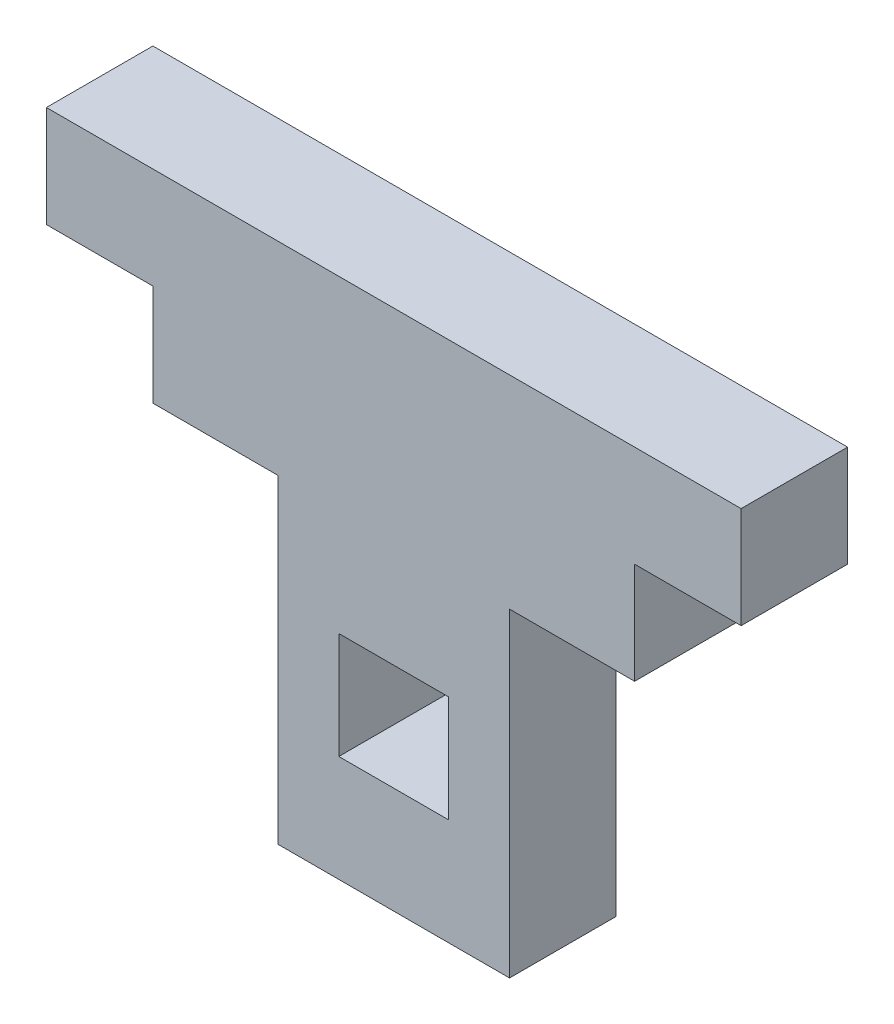
SolidWorks part; units mm, degrees
ref_plane "Front Plane" through (0, 0, 0) normal (0, 0, 1) x (1, 0, 0)
ref_plane "Top Plane" through (0, 0, 0) normal (0, 1, 0) x (1, 0, 0)
ref_plane "Right Plane" through (0, 0, 0) normal (1, 0, 0) x (0, 0, -1)
sketch "Sketch1" plane through (0, 0, 0) normal (0, 0, 1) x (1, 0, 0)
  line L5 (0, 0) -> (24.13, 0)
  line L6 (0, 0) -> (0, 10.16)
  line L7 (0, 10.16) -> (24.13, 10.16)
  line L8 (24.13, 0) -> (24.13, 10.16)
  dimension "D1" = 24.13
  dimension "D2" = 10.16
extrude "Boss-Extrude1" add sketch "Sketch1" along normal blind 5.334 contours L6 L5 L8 L7
sketch "Sketch6" plane through (24.13, 0, 0) normal (1, 0, 0) x (0, 0, -1)
  line L9 (-5.334, 0) -> (-5.334, 10.16) construction
  line L10 (-5.334, 10.16) -> (0, 10.16)
  line L11 (-5.334, 10.16) -> (-5.334, 0)
  line L12 (-5.334, 0) -> (0, 0)
  line L13 (0, 10.16) -> (0, 0)
  line L14 (-5.334, 10.16) -> (0, 10.16) construction
extrude "Boss-Extrude5" add sketch "Sketch6" along normal blind 5.334
sketch "Sketch11" plane through (0, 0, 0) normal (-1, 0, 0) x (0, 0, 1)
  line L1 (0, 10.2062) -> (5.334, 10.2062)
  line L2 (0, 10.2062) -> (0, 0)
  line L3 (0, 0) -> (5.334, 0)
  line L4 (5.334, 10.2062) -> (5.334, 0)
extrude "Boss-Extrude6" add sketch "Sketch11" along normal blind 5.334
sketch "Sketch12" plane through (0, 0, 0) normal (0, -1, 0) x (-1, 0, 0)
  line L1 (-29.464, 0) -> (5.334, 0)
  line L2 (-29.464, 0) -> (-29.464, -5.334)
  line L3 (-29.464, -5.334) -> (5.334, -5.334)
  line L4 (5.334, 0) -> (5.334, -5.334)
extrude "Boss-Extrude7" add sketch "Sketch12" along normal blind 5.334
sketch "Sketch13" plane through (0, 0, 0) normal (0, 0, -1) x (-1, 0, 0)
  line L0 (0, 10.16) -> (5.334, 10.16)
  line L1 (5.334, 10.2062) -> (5.334, -5.334) construction
  line L2 (0, 10.16) -> (0, 10.2062)
  line L3 (5.334, 10.2062) -> (0, 10.2062) construction
  line L4 (0, 10.2062) -> (5.334, 10.2062)
  line L5 (5.334, 10.2062) -> (5.334, 10.16)
extrude "Cut-Extrude1" cut sketch "Sketch13" against normal through all
sketch "Sketch17" plane through (0, -5.334, 0) normal (0, -1, 0) x (-1, 0, 0)
  line L0 (-29.464, -5.334) -> (5.334, -5.334) construction
  line L1 (5.334, 0) -> (-6.2653, 0)
  line L2 (5.334, 0) -> (5.334, -5.334)
  line L3 (5.334, -5.334) -> (-6.2653, -5.334)
  line L4 (-6.2653, 0) -> (-6.2653, -5.334)
  line L5 (-17.8647, 0) -> (-6.2653, 0) construction
  line L6 (-29.464, 0) -> (-17.8647, 0)
  line L7 (-29.464, 0) -> (-29.464, -5.334)
  line L8 (-29.464, -5.334) -> (-17.8647, -5.334)
  line L9 (-17.8647, 0) -> (-17.8647, -5.334)
extrude "Cut-Extrude5" cut sketch "Sketch17" against normal blind 5.334
sketch "Sketch18" plane through (0, 0, 5.334) normal (0, 0, 1) x (1, 0, 0)
  line L0 (17.78, 63.5) -> (17.78, 5.08) construction
  line L1 (-5.334, 10.16) -> (0, 10.16)
  line L2 (-5.334, 10.16) -> (-5.334, 5.08)
  line L3 (-5.334, 5.08) -> (0, 5.08)
  line L4 (0, 10.16) -> (0, 5.08)
  line L5 (17.78, 5.08) -> (29.464, 5.08)
  line L6 (17.78, 5.08) -> (17.78, 10.16)
  line L7 (17.78, 10.16) -> (29.464, 10.16)
  line L8 (29.464, 5.08) -> (29.464, 10.16)
extrude "Cut-Extrude6" cut sketch "Sketch18" against normal blind 5.334
sketch "Sketch19" plane through (17.78, 0, 0) normal (1, 0, 0) x (0, 0, -1)
  line L1 (-5.334, 10.16) -> (0, 10.16)
  line L2 (-5.334, 10.16) -> (-5.334, 5.08)
  line L3 (-5.334, 5.08) -> (0, 5.08)
  line L4 (0, 10.16) -> (0, 5.08)
extrude "Boss-Extrude8" add sketch "Sketch19" along normal blind 5.334
sketch "Sketch20" plane through (23.114, 0, 0) normal (1, 0, 0) x (0, 0, -1)
  line L1 (-5.334, 10.16) -> (0, 10.16)
  line L2 (-5.334, 10.16) -> (-5.334, 5.08)
  line L3 (-5.334, 5.08) -> (0, 5.08)
  line L4 (0, 10.16) -> (0, 5.08)
extrude "Boss-Extrude10" add sketch "Sketch20" along normal blind 1.016
sketch "Sketch21" plane through (0, -5.334, 0) normal (0, -1, 0) x (1, 0, 0)
  line L1 (6.2653, 5.334) -> (17.8647, 5.334)
  line L2 (6.2653, 5.334) -> (6.2653, 0)
  line L3 (6.2653, 0) -> (17.8647, 0)
  line L4 (17.8647, 5.334) -> (17.8647, 0)
extrude "Boss-Extrude11" add sketch "Sketch21" along normal blind 10.668
sketch "Sketch22" plane through (0, 0, 5.334) normal (0, 0, 1) x (1, 0, 0)
  line L0 (17.8647, -16.002) -> (6.2653, -16.002) construction
  line L1 (9.3133, -5.334) -> (14.8167, -5.334)
  line L2 (9.3133, -5.334) -> (9.3133, -10.668)
  line L3 (9.3133, -10.668) -> (14.8167, -10.668)
  line L4 (14.8167, -5.334) -> (14.8167, -10.668)
  line L5 (17.8647, 0) -> (17.8647, -16.002) construction
  line L6 (6.2653, 0) -> (6.2653, -16.002) construction
  dimension "D1" = 5.334
  dimension "D2" = 5.334
  dimension "D3" = 3.048
  dimension "D4" = 3.048
extrude "Cut-Extrude7" cut sketch "Sketch22" against normal through all
sketch "Sketch23" plane through (0, 0, 0) normal (-1, 0, 0) x (0, 0, 1)
  line L1 (0, 5.08) -> (5.334, 5.08)
  line L2 (0, 5.08) -> (0, 10.16)
  line L3 (0, 10.16) -> (5.334, 10.16)
  line L4 (5.334, 5.08) -> (5.334, 10.16)
extrude "Boss-Extrude12" add sketch "Sketch23" along normal blind 5.334
sketch "Sketch24" plane through (-5.334, 0, 0) normal (-1, 0, 0) x (0, 0, 1)
  line L0 (5.334, 0) -> (0, 0) construction
  line L1 (5.334, 0) -> (0, 0)
  line L2 (5.334, 0) -> (5.334, 5.08)
  line L3 (5.334, 5.08) -> (0, 5.08)
  line L4 (0, 0) -> (0, 5.08)
  line L5 (0, 10.16) -> (0, 0) construction
  dimension "D1" = 5.08
extrude "Cut-Extrude8" cut sketch "Sketch24" against normal blind 5.334
sketch "Sketch25" plane through (24.13, 0, 0) normal (1, 0, 0) x (0, 0, -1)
  line L1 (-5.334, 10.16) -> (0, 10.16)
  line L2 (-5.334, 10.16) -> (-5.334, 5.08)
  line L3 (-5.334, 5.08) -> (0, 5.08)
  line L4 (0, 10.16) -> (0, 5.08)
extrude "Boss-Extrude13" add sketch "Sketch25" along normal blind 5.334
sketch "Sketch26" plane through (29.464, 0, 0) normal (1, 0, 0) x (0, 0, -1)
  line L0 (0, 0) -> (0, 10.16) construction
  line L1 (-5.334, 0) -> (0, 0)
  line L2 (-5.334, 0) -> (-5.334, 5.08)
  line L3 (-5.334, 5.08) -> (0, 5.08)
  line L4 (0, 0) -> (0, 5.08)
  dimension "D1" = 5.08
extrude "Cut-Extrude9" cut sketch "Sketch26" against normal blind 5.334
equation "\"Foamcore\"= .1875in"
equation "\"Mdf\"= .21in"
equation "\"Gmaterial\"= \"Mdf\""
equation "\"D1@Boss-Extrude1\"= \"Gmaterial\""
equation "\"D1@Boss-Extrude7\"= \"Gmaterial\""
equation "\"D1@Boss-Extrude6\"= \"Gmaterial\""
equation "\"D1@Boss-Extrude5\"= \"Gmaterial\""
equation "\"D1@Cut-Extrude5\"=\"Gmaterial\""
equation "\"D1@Cut-Extrude6\"=\"Gmaterial\""
equation "\"D1@Boss-Extrude8\"=\"Gmaterial\""
